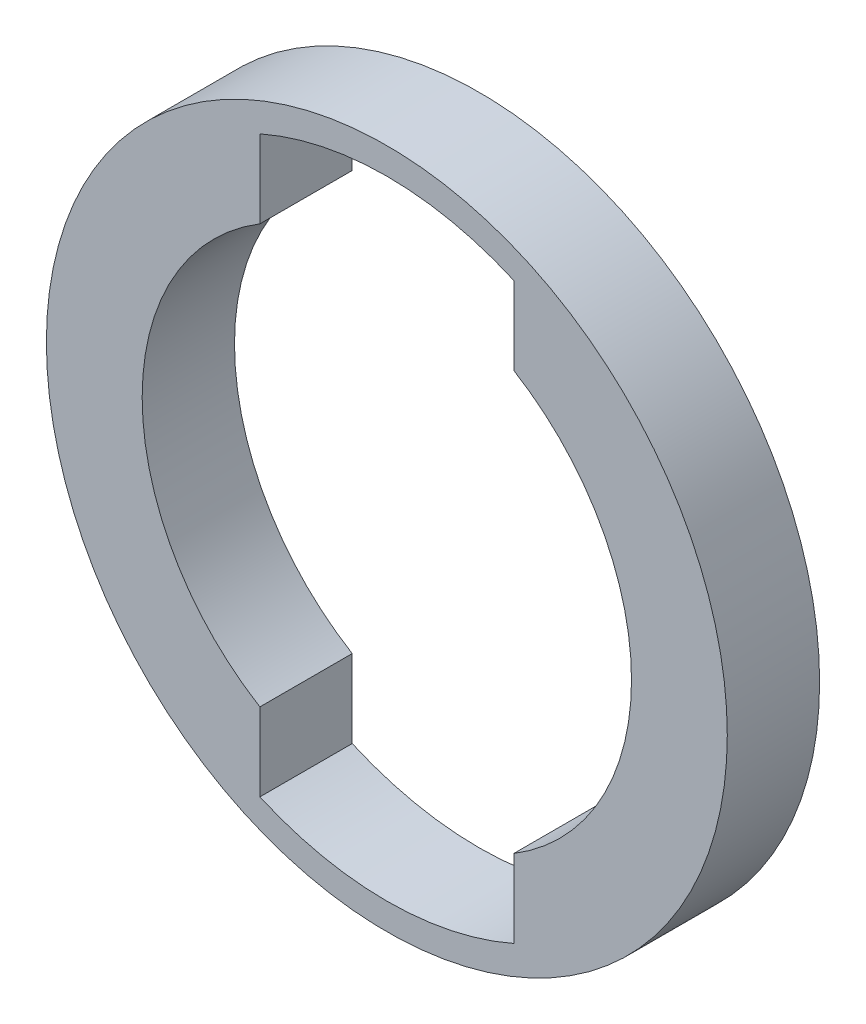
SolidWorks part; units mm, degrees
material "Rubber"
ref_plane "Front Plane" through (0, 0, 0) normal (0, 0, 1) x (1, 0, 0)
ref_plane "Top Plane" through (0, 0, 0) normal (0, 1, 0) x (1, 0, 0)
ref_plane "Right Plane" through (0, 0, 0) normal (1, 0, 0) x (0, 0, -1)
sketch "Sketch3" plane through (0, 0, 0) normal (0, 0, 1) x (1, 0, 0)
  line L0 (0, 8.6628) -> (0, -10.0092) construction
  line L1 (-2.75, 6.2191) -> (-2.75, 4.5307)
  line L2 (2.75, 6.2191) -> (2.75, 4.5307)
  line L3 (-1.505, 0) -> (1.8163, 0) construction
  line L4 (2.75, -6.2191) -> (2.75, -4.5307)
  line L5 (-2.75, -6.2191) -> (-2.75, -4.5307)
  circle A0 centre (0, 0) radius 7.375
  arc A1 (-2.75, -6.2191) -> (2.75, -6.2191) centre (0, 0) ccw
  arc A2 (-2.75, 4.5307) -> (-2.75, -4.5307) centre (0, 0) ccw
  arc A3 (2.75, -4.5307) -> (2.75, 4.5307) centre (0, 0) ccw
  arc A4 (2.75, 6.2191) -> (-2.75, 6.2191) centre (0, 0) ccw
  dimension "D1" = 14.75
  dimension "D2" = 13.6
  dimension "D3" = 10.6
  dimension "D4" = 2.75
extrude "Boss-Extrude1" add sketch "Sketch3" against normal blind 2
